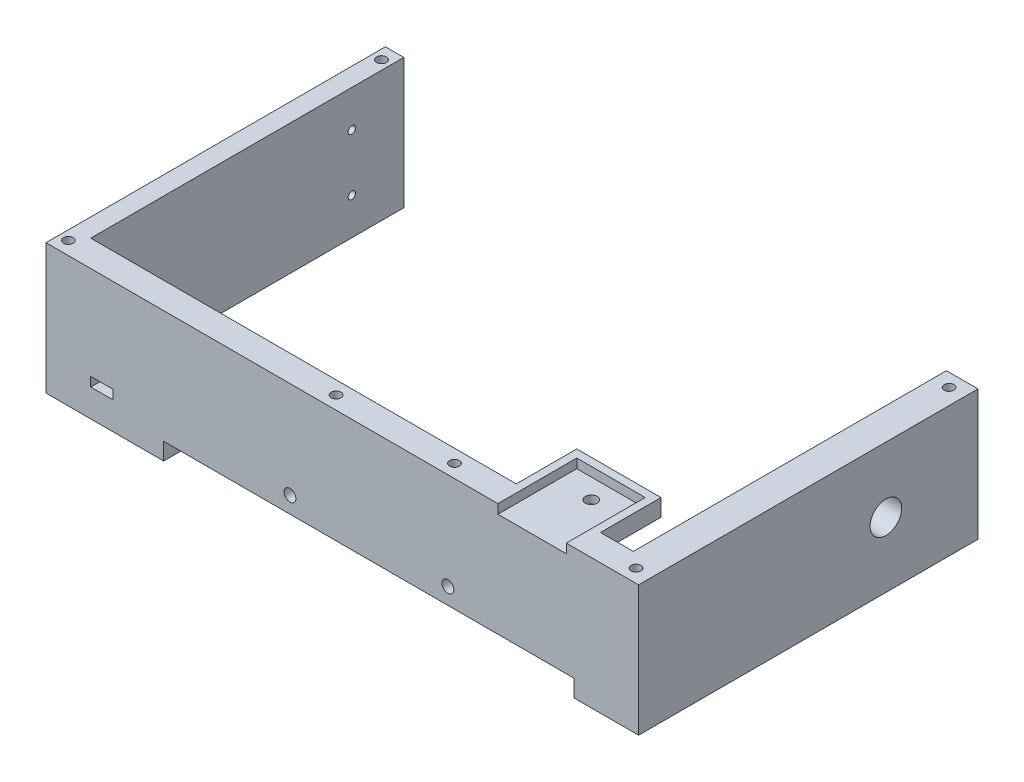
SolidWorks part; units mm, degrees
ref_plane "Front Plane" through (0, 0, 0) normal (0, 0, 1) x (1, 0, 0)
ref_plane "Top Plane" through (0, 0, 0) normal (0, 1, 0) x (1, 0, 0)
ref_plane "Right Plane" through (0, 0, 0) normal (1, 0, 0) x (0, 0, -1)
sketch "Sketch1" plane through (0, 0, 0) normal (1, 0, 0) x (0, 0, -1)
  line L1 (0, 0) -> (129, 0)
  line L6 (129, 55.5) -> (129, 0)
  line L10 (0, 0) -> (0, 55.5)
  line L12 (0, 55.5) -> (129, 55.5)
  dimension "D1" = 129
  dimension "D2" = 55.5
extrude "Boss-Extrude1" add sketch "Sketch1" along normal mid plane 196.24
sketch "Sketch18" plane through (-98.12, 0, 0) normal (-1, 0, 0) x (0, 0, 1)
  line L1 (-129, 0) -> (0, 0)
  line L2 (-129, 0) -> (-129, 55.5)
  line L3 (-129, 55.5) -> (0, 55.5)
  line L4 (0, 0) -> (0, 55.5)
  line L5 (-129, 55.5) -> (0, 55.5) construction
  line L6 (-129, 55.5) -> (0, 55.5) construction
  line L7 (0, 55.5) -> (0, 0) construction
extrude "Boss-Extrude9" add sketch "Sketch18" along normal blind 29
sketch "Sketch33" plane through (0, 0, 0) normal (0, 0, 1) x (1, 0, 0)
  line L1 (73.62, 0) -> (-82.38, 0)
  line L2 (73.62, 0) -> (73.62, 12.5)
  line L4 (-82.38, 0) -> (-82.38, 12.5)
  line L8 (98.12, 55.5) -> (98.12, 0) construction
  line L9 (98.12, 0) -> (-127.12, 0) construction
  line L10 (-82.38, 12.5) -> (73.62, 12.5)
  dimension "D1" = 156
  dimension "D2" = 12.5
  dimension "D4" = 24.5
extrude "Cut-Extrude8" cut sketch "Sketch33" against normal offset from surface (20.5 mm away) 108.5 up to face at (-14.5, 27.75, -129)
sketch "Sketch40" plane through (0, 0, -129) normal (0, 0, -1) x (-1, 0, 0)
  line L0 (-98.12, 0) -> (-98.12, 55.5) construction
  line L1 (-86.12, 6) -> (120.12, 6)
  line L2 (-86.12, 6) -> (-86.12, 55.5)
  line L3 (-86.12, 55.5) -> (120.12, 55.5)
  line L4 (120.12, 6) -> (120.12, 55.5)
  line L6 (-98.12, 55.5) -> (127.12, 55.5) construction
  line L7 (-98.12, 0) -> (127.12, 0) construction
  line L12 (127.12, 55.5) -> (127.12, 0) construction
  dimension "D1" = 12
  dimension "D2" = 7
  dimension "D3" = 6
extrude "Cut-Extrude9" cut sketch "Sketch40" against normal blind 119
sketch "Sketch62" plane through (0, 0, 0) normal (0, 0, 1) x (1, 0, 0)
  line L0 (-127.12, 0) -> (-127.12, 55.5) construction
  line L1 (-110.12, 20) -> (-101.62, 20)
  line L2 (-110.12, 20) -> (-110.12, 16.5)
  line L3 (-110.12, 16.5) -> (-101.62, 16.5)
  line L4 (-101.62, 20) -> (-101.62, 16.5)
  line L5 (73.62, 12.5) -> (-82.38, 12.5) construction
  dimension "D1" = 3.5
  dimension "D2" = 8.5
  dimension "D3" = 17
  dimension "D4" = 4
extrude "Cut-Extrude18" cut sketch "Sketch62" against normal up to next
hole_wizard "M4 Clearance Hole2" positions "Sketch66" profile "Sketch67" hole size "M4" standard "ANSI Metric" end condition through all
sketch "Sketch66" plane through (0, 0, 0) normal (0, 0, 1) x (1, 0, 0)
  point P0 (-34.375, 18.75)
  point P2 (25.625, 18.75)
sketch "Sketch67" plane through (-34.375, 18.75, 0) normal (1, 0, 0) x (0, -1, 0)
  line L0 (0, 0) -> (0, 129)
  line L1 (0, 129) -> (2.25, 129)
  line L2 (2.25, 129) -> (2.25, 0)
  line L5 (2.25, 0) -> (0, 0)
  line L11 (0, -6.35) -> (0, 107.95) construction
  dimension "Thru Hole Dia." = 4.5
  dimension "Thru Hole Depth" = 129
hole_wizard "#2 (0.221) Diameter Hole1" positions "Sketch68" profile "Sketch69" hole size "#2" standard "ANSI Inch"
sketch "Sketch68" plane through (0, 0, -129) normal (0, 0, -1) x (-1, 0, 0)
  point P0 (-91.5731, 38.6875)
  point P2 (-91.5731, 22.8125)
sketch "Sketch69" plane through (91.5731, 38.6875, -129) normal (1, 0, 0) x (0, 1, 0)
  line L0 (0, 0) -> (0, 20.7511)
  line L1 (0, 20.7511) -> (1.25, 20)
  line L2 (1.25, 20) -> (1.25, 0)
  line L5 (1.25, 0) -> (0, 0)
  line L10 (0, 20.7511) -> (-1.25, 20) construction
  line L11 (0, -6.35) -> (0, 107.95) construction
  dimension "Hole Dia." = 2.5
  dimension "Hole Depth" = 20
  dimension "Drill Angle" = 118
sketch "Sketch70" plane through (0, 0, -10) normal (0, 0, -1) x (-1, 0, 0)
  line L1 (-73.63, 55.5) -> (-41.63, 55.5)
  line L2 (-73.63, 55.5) -> (-73.63, 49)
  line L3 (-73.63, 49) -> (-41.63, 49)
  line L4 (-41.63, 55.5) -> (-41.63, 49)
  line L12 (120.12, 55.5) -> (-86.12, 55.5) construction
  line L13 (-86.12, 55.5) -> (-86.12, 6) construction
  dimension "D1" = 12.49
  dimension "D2" = 32
  dimension "D3" = 6.5
extrude "Boss-Extrude10" add sketch "Sketch70" along normal blind 23
sketch "Sketch71" plane through (0, 0, 0) normal (0, 0, 1) x (1, 0, 0)
  line L0 (98.12, 55.5) -> (-127.12, 55.5) construction
  line L1 (70.63, 55.5) -> (44.63, 55.5)
  line L2 (70.63, 55.5) -> (70.63, 52)
  line L3 (70.63, 52) -> (44.63, 52)
  line L4 (44.63, 55.5) -> (44.63, 52)
  line L5 (98.12, 55.5) -> (98.12, 0) construction
  dimension "D1" = 26
  dimension "D2" = 3.5
  dimension "D3" = 27.49
extrude "Cut-Extrude19" cut sketch "Sketch71" against normal blind 30
sketch "Sketch73" plane through (0, 0, -129) normal (0, 0, -1) x (-1, 0, 0)
  line L0 (127.12, 55.5) -> (127.12, 0) construction
  line L1 (-98.12, 0) -> (127.12, 0)
  line L2 (-98.12, 0) -> (-98.12, 6)
  line L3 (-98.12, 6) -> (127.12, 6)
  line L4 (127.12, 0) -> (127.12, 6)
  line L5 (-86.12, 6) -> (120.12, 6) construction
extrude "Cut-Extrude20" cut sketch "Sketch73" against normal through all
hole_wizard "Ø3.7 (3.7) Diameter Hole1" positions "Sketch74" profile "Sketch75" hole size "Ø3.7" standard "ANSI Metric"
sketch "Sketch74" plane through (0, 55.5, 0) normal (0, 1, 0) x (1, 0, 0)
  line L7 (92.12, 124) -> (92.12, 5) construction
  line L9 (98.12, 64.5) -> (92.12, 64.5) construction
  line L10 (98.12, 129) -> (98.12, 0) construction
  line L12 (92.12, 124) -> (92.12, 129) construction
  line L13 (98.12, 129) -> (86.12, 129) construction
  line L30 (92.12, 5) -> (23.14, 5) construction
  line L36 (-123.62, 129) -> (-123.62, 0) construction
  line L37 (-120.12, 129) -> (-127.12, 129) construction
  line L38 (44.63, 0) -> (-127.12, 0) construction
  line L40 (98.12, 0) -> (70.63, 0) construction
  line L41 (57.63, 0) -> (57.63, 5) construction
  line L42 (44.63, 0) -> (70.63, 0) construction
  point P0 (92.12, 124)
  point P2 (92.12, 5)
  point P4 (-123.62, 124)
  point P6 (-123.62, 5)
  point P8 (23.14, 5)
  point P10 (-21.86, 5)
  dimension "D1" = 5
  dimension "D2" = 45
sketch "Sketch75" plane through (92.12, 55.5, -124) normal (1, 0, 0) x (0, 0, 1)
  line L0 (0, 0) -> (0, 13.1116)
  line L1 (0, 13.1116) -> (1.85, 12)
  line L2 (1.85, 12) -> (1.85, 0)
  line L5 (1.85, 0) -> (0, 0)
  line L10 (0, 13.1116) -> (-1.85, 12) construction
  line L11 (0, -6.35) -> (0, 107.95) construction
  dimension "Hole Dia." = 3.7
  dimension "Hole Depth" = 12
  dimension "Drill Angle" = 118
hole_wizard "Ø3.7 (3.7) Diameter Hole2" positions "Sketch76" profile "Sketch77" hole size "Ø3.7" standard "ANSI Metric"
sketch "Sketch76" plane through (0, 6, 0) normal (0, -1, 0) x (-1, 0, 0)
  circle A0 centre (123.62, 124) radius 1.85 construction
  circle A1 centre (123.62, 5) radius 1.85 construction
  circle A2 centre (-92.12, 5) radius 1.85 construction
  circle A3 centre (-92.12, 124) radius 1.85 construction
  point P0 (-92.12, 124)
  point P2 (-92.12, 5)
  point P4 (123.62, 5)
  point P6 (123.62, 124)
sketch "Sketch77" plane through (92.12, 6, -124) normal (1, 0, 0) x (0, 0, -1)
  line L0 (0, 0) -> (0, 13.1116)
  line L1 (0, 13.1116) -> (1.85, 12)
  line L2 (1.85, 12) -> (1.85, 0)
  line L5 (1.85, 0) -> (0, 0)
  line L10 (0, 13.1116) -> (-1.85, 12) construction
  line L11 (0, -6.35) -> (0, 107.95) construction
  dimension "Hole Dia." = 3.7
  dimension "Hole Depth" = 12
  dimension "Drill Angle" = 118
hole_wizard "M4 Clearance Hole3" positions "Sketch78" profile "Sketch79" hole size "M4" standard "ANSI Metric"
sketch "Sketch78" plane through (0, 52, 0) normal (0, 1, 0) x (1, 0, 0)
  point P0 (57.63, 22.5)
sketch "Sketch79" plane through (57.63, 52, -22.5) normal (1, 0, 0) x (0, 0, 1)
  line L0 (0, 0) -> (0, 13.3519)
  line L1 (0, 13.3519) -> (2.25, 12)
  line L2 (2.25, 12) -> (2.25, 0)
  line L5 (2.25, 0) -> (0, 0)
  line L10 (0, 13.3519) -> (-2.25, 12) construction
  line L11 (0, -6.35) -> (0, 107.95) construction
  dimension "Hole Dia." = 4.5
  dimension "Hole Depth" = 12
  dimension "Drill Angle" = 118
hole_wizard "#3 Clearance Hole1" positions "Sketch80" profile "Sketch81" hole size "#3" standard "ANSI Inch"
sketch "Sketch80" plane through (-127.12, 0, 0) normal (-1, 0, 0) x (0, 0, 1)
  line L0 (-111.2, 41.5) -> (-107.3, 41.5) construction
  line L2 (-111.2, 20) -> (-107.3, 20) construction
  point P0 (-109.25, 41.5)
  point P2 (-109.25, 20)
sketch "Sketch81" plane through (-127.12, 41.5, -109.25) normal (0, 1, 0) x (0, 0, 1)
  line L0 (0, 0) -> (0, 7)
  line L1 (0, 7) -> (1.397, 7)
  line L2 (1.397, 7) -> (1.397, 0)
  line L5 (1.397, 0) -> (0, 0)
  line L11 (0, -6.35) -> (0, 107.95) construction
  dimension "Thru Hole Dia." = 2.794
  dimension "Thru Hole Depth" = 7
hole_wizard "Ø12.0mm Dowel Hole1" positions "Sketch82" profile "Sketch83" hole size "Ø12.0" standard "ANSI Metric"
sketch "Sketch82" plane through (86.12, 0, 0) normal (-1, 0, 0) x (0, 0, 1)
  line L0 (-129, 30.75) -> (-94, 30.75) construction
  line L1 (-129, 55.5) -> (-129, 6) construction
  point P0 (-94, 30.75)
  dimension "D1" = 35
sketch "Sketch83" plane through (86.12, 30.75, -94) normal (0, 1, 0) x (0, 0, 1)
  line L0 (0, 0) -> (0, 12)
  line L1 (0, 12) -> (6, 12)
  line L2 (6, 12) -> (6, 0)
  line L5 (6, 0) -> (0, 0)
  line L11 (0, -6.35) -> (0, 107.95) construction
  dimension "Thru Hole Dia." = 12
  dimension "Thru Hole Depth" = 12
